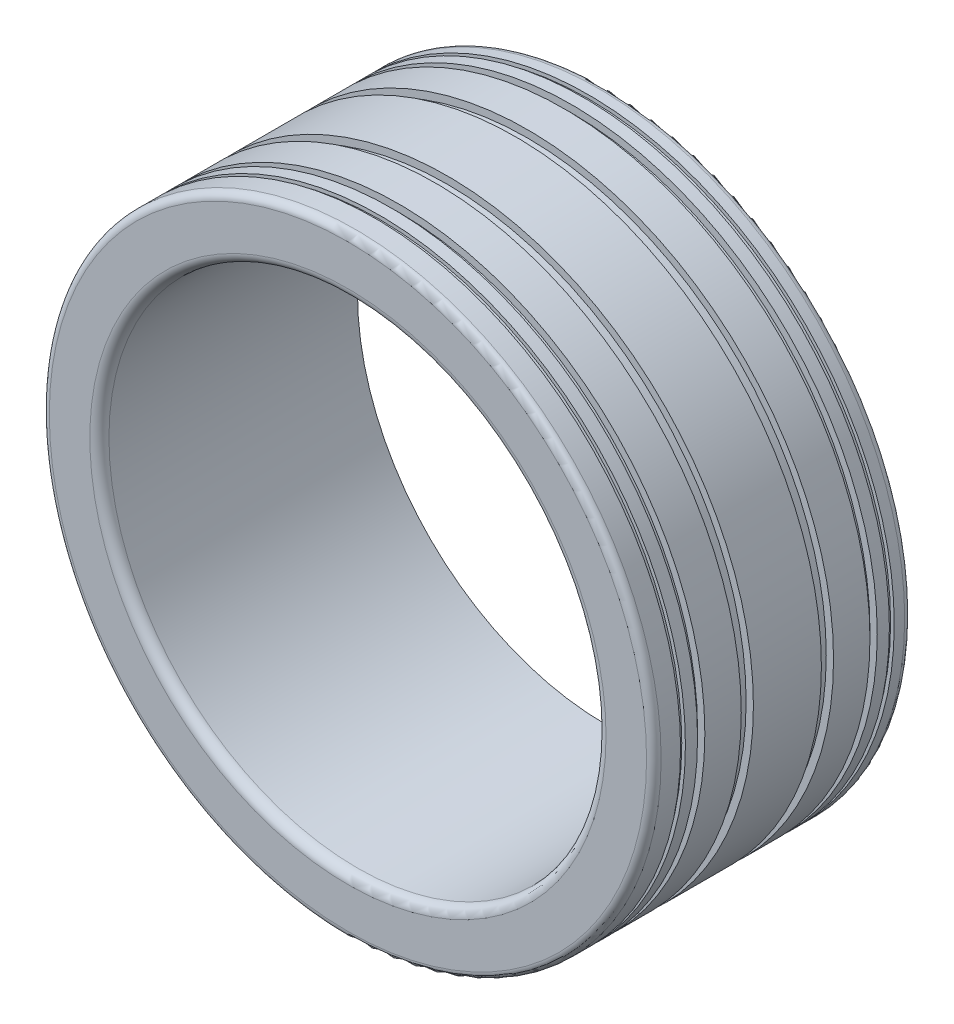
SolidWorks part; units mm, degrees
material "Caucho"
ref_plane "Alzado" through (0, 0, 0) normal (0, 0, 1) x (1, 0, 0)
ref_plane "Planta" through (0, 0, 0) normal (0, 1, 0) x (1, 0, 0)
ref_plane "Vista lateral" through (0, 0, 0) normal (1, 0, 0) x (0, 0, -1)
sketch "Croquis1" plane through (0, 0, 0) normal (0, 0, 1) x (1, 0, 0)
  circle A0 centre (0, 0) radius 32
  circle A1 centre (0, 0) radius 26
  dimension "D1" = 64
  dimension "D2" = 52
extrude "Saliente-Extruir1" add sketch "Croquis1" against normal blind 27
fillet "Redondeo1" radius 0.762 2 edges at (32, 0, -27) (32, 0, 0)
sketch "Croquis2" plane through (0, 0, 0) normal (0, 1, 0) x (1, 0, 0)
  line L0 (-32, 0) -> (32, 0) construction
  line L1 (-32, 0) -> (32, 0) construction
  line L2 (-32, 0) -> (-32, 27.94) construction
  line L3 (-32, 13.97) -> (35.56, 13.97) construction
  line L4 (-32, 23.368) -> (-31.238, 23.368)
  line L5 (-32, 23.368) -> (-32, 22.606)
  line L6 (-32, 22.606) -> (-31.238, 22.606)
  line L7 (-31.238, 23.368) -> (-31.238, 22.606)
  line L8 (-32, 18.796) -> (-31.238, 18.796)
  line L9 (-32, 18.796) -> (-32, 17.526)
  line L10 (-32, 17.526) -> (-31.238, 17.526)
  line L11 (-31.238, 18.796) -> (-31.238, 17.526)
  line L12 (-32, 25.146) -> (-31.619, 25.146)
  line L13 (-32, 25.146) -> (-32, 24.638)
  line L14 (-32, 24.638) -> (-31.619, 24.638)
  line L15 (-31.619, 25.146) -> (-31.619, 24.638)
  line L16 (-32, 9.144) -> (-31.238, 9.144)
  line L17 (-32, 9.144) -> (-32, 10.414)
  line L18 (-32, 10.414) -> (-31.238, 10.414)
  line L19 (-31.238, 9.144) -> (-31.238, 10.414)
  line L20 (-32, 4.572) -> (-32, 5.334)
  line L21 (-32, 5.334) -> (-31.238, 5.334)
  line L22 (-31.238, 4.572) -> (-31.238, 5.334)
  line L23 (-32, 4.572) -> (-31.238, 4.572)
  line L24 (-32, 2.794) -> (-32, 3.302)
  line L25 (-32, 2.794) -> (-31.619, 2.794)
  line L26 (-31.619, 2.794) -> (-31.619, 3.302)
  line L27 (-32, 3.302) -> (-31.619, 3.302)
  line L28 (0, 0) -> (0, 27.94) construction
  dimension "D1" = 27.94
  dimension "D2" = 0.762
  dimension "D3" = 0.381
  dimension "D4" = 1.27
  dimension "D5" = 0.508
  dimension "D6" = 2.794
  dimension "D7" = 1.27
  dimension "D8" = 3.81
  dimension "D9" = 0.762
revolve "Cortar-Revolución1" cut sketch "Croquis2" angle 360 about L28
fillet "Fillet1" radius 1 1 edges at (26, 0, 0)
